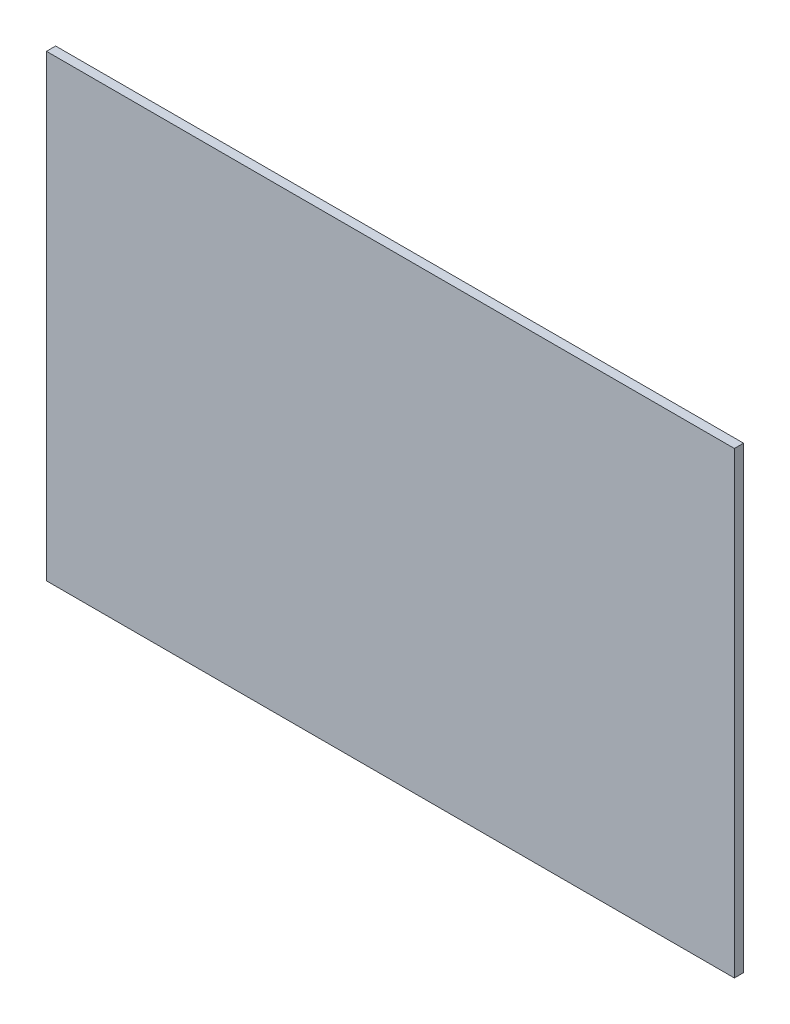
SolidWorks part; units mm, degrees
ref_plane "Front Plane" through (0, 0, 0) normal (0, 0, 1) x (1, 0, 0)
ref_plane "Top Plane" through (0, 0, 0) normal (0, 1, 0) x (1, 0, 0)
ref_plane "Right Plane" through (0, 0, 0) normal (1, 0, 0) x (0, 0, -1)
sketch "Sketch1" plane through (0, 0, 0) normal (0, 0, 1) x (1, 0, 0)
  line L0 (-352.6531, 0) -> (547.3469, 0) construction
  line L1 (-352.6531, 0) -> (547.3469, 0)
  line L2 (-352.6531, 0) -> (-352.6531, 600)
  line L3 (-352.6531, 600) -> (547.3469, 600)
  line L4 (547.3469, 0) -> (547.3469, 600)
  line L5 (547.3469, 600) -> (547.3469, 0) construction
extrude "Boss-Extrude1" add sketch "Sketch1" against normal blind 12 contours L3 L4 L1 L2
